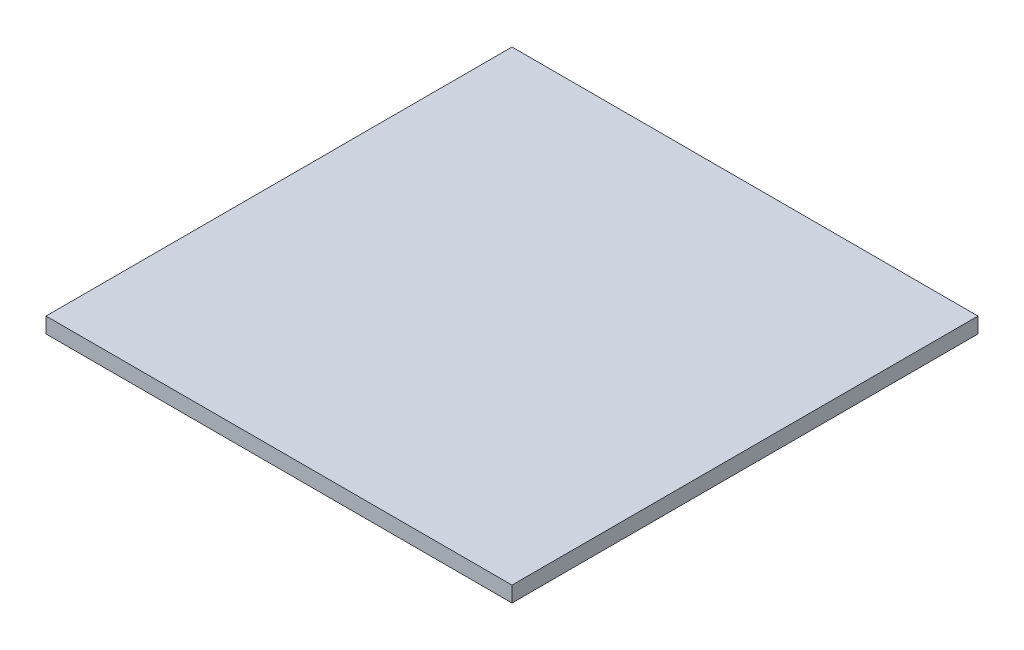
SolidWorks part; units mm, degrees
ref_plane "Front Plane" through (0, 0, 0) normal (0, 0, 1) x (1, 0, 0)
ref_plane "Top Plane" through (0, 0, 0) normal (0, 1, 0) x (1, 0, 0)
ref_plane "Right Plane" through (0, 0, 0) normal (1, 0, 0) x (0, 0, -1)
sketch "Sketch1" plane through (0, 0, 0) normal (0, 1, 0) x (1, 0, 0)
  line L1 (0, 0) -> (76.2, 0)
  line L2 (0, 0) -> (0, 76.2)
  line L3 (0, 76.2) -> (76.2, 76.2)
  line L4 (76.2, 0) -> (76.2, 76.2)
  dimension "D1" = 76.2
  dimension "D2" = 76.2
extrude "Boss-Extrude1" add sketch "Sketch1" along normal blind 2.54
